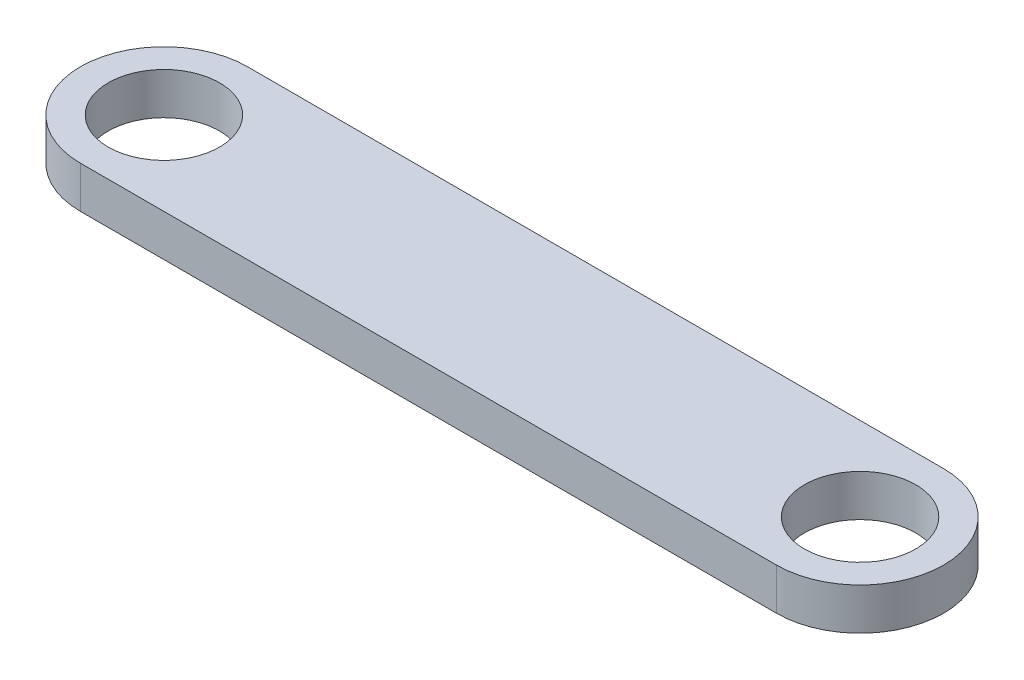
SolidWorks part; units mm, degrees
ref_plane "Front Plane" through (0, 0, 0) normal (0, 0, 1) x (1, 0, 0)
ref_plane "Top Plane" through (0, 0, 0) normal (0, 1, 0) x (1, 0, 0)
ref_plane "Right Plane" through (0, 0, 0) normal (1, 0, 0) x (0, 0, -1)
sketch "Sketch1" plane through (0, 0, 0) normal (0, 1, 0) x (1, 0, 0)
  line L0 (-40.1246, 6.1246) -> (9.8754, 6.1246)
  line L1 (-40.1246, -5.8754) -> (9.8754, -5.8754)
  circle A0 centre (-40.1246, 0.1246) radius 4
  circle A1 centre (9.8754, 0.1246) radius 4
  arc A2 (-40.1246, 6.1246) -> (-40.1246, -5.8754) centre (-40.1246, 0.1246) ccw
  arc A3 (9.8754, -5.8754) -> (9.8754, 6.1246) centre (9.8754, 0.1246) ccw
  dimension "D2" = 8
  dimension "D3" = 8
  dimension "D1" = 50
  dimension "D4" = 50
  dimension "D5" = 50
extrude "Boss-Extrude1" add sketch "Sketch1" along normal blind 3
